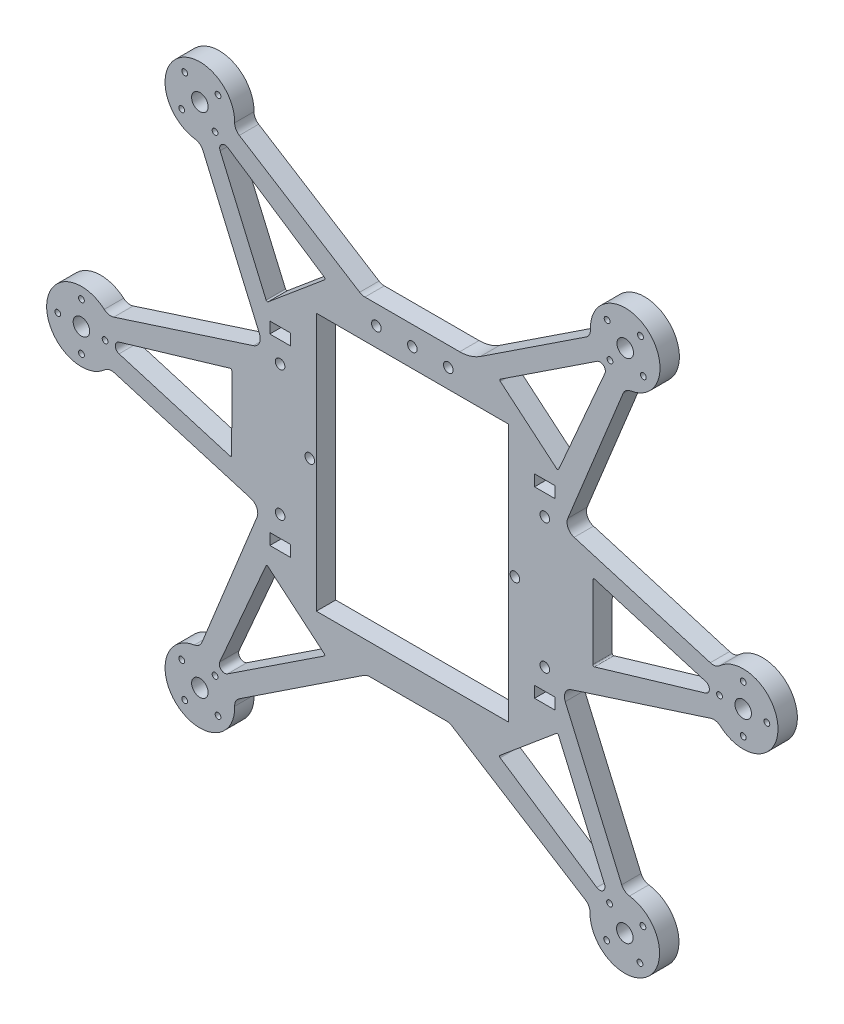
SolidWorks part; units mm, degrees
ref_plane "Front Plane" through (0, 0, 0) normal (0, 0, 1) x (1, 0, 0)
ref_plane "Top Plane" through (0, 0, 0) normal (0, 1, 0) x (1, 0, 0)
ref_plane "Right Plane" through (0, 0, 0) normal (1, 0, 0) x (0, 0, -1)
sketch "Sketch1" plane through (0, 0, 0) normal (0, 0, 1) x (1, 0, 0)
  line L0 (595.5776, 440.4192) -> (595.6011, 462.6566)
  line L1 (550.1603, 451.4897) -> (550.1603, 458.6435) construction
  line L2 (607.0986, 422.6607) -> (613.2986, 426.0607) construction
  line L3 (610.1986, 424.3607) -> (610.1986, 432.3607) construction
  line L4 (610.1986, 432.3607) -> (610.1986, 424.3607) construction
  line L5 (607.0986, 426.0607) -> (613.2986, 422.6607) construction
  line L6 (561.5223, 453.1038) -> (595.092, 463.0374)
  line L7 (561.5198, 450.0321) -> (595.073, 440.0434)
  line L8 (550.1603, 451.4897) -> (557.3141, 451.4897) construction
  line L9 (623.5557, 402.561) -> (606.5359, 416.873)
  line L10 (607.0986, 426.0607) -> (607.0986, 422.6607)
  line L11 (607.0986, 426.0607) -> (613.2986, 426.0607)
  line L12 (613.2986, 426.0607) -> (613.2986, 422.6607)
  line L13 (591.9484, 384.6267) -> (605.917, 416.7277)
  line L14 (603.9549, 476.5225) -> (586.8769, 515.9464)
  line L15 (594.2998, 382.6503) -> (623.5192, 401.9329)
  line L16 (607.0986, 422.6607) -> (613.2986, 422.6607)
  line L17 (706.0206, 520.3291) -> (676.8012, 501.0464)
  line L18 (635.8428, 502.057) -> (664.4776, 502.057)
  line L19 (592.0667, 518.4553) -> (605.9825, 486.3314)
  line L20 (637.2391, 403.4095) -> (660.5203, 403.4093)
  line L21 (690.1986, 470.2607) -> (690.1986, 433.8107) construction
  line L22 (693.2986, 481.4107) -> (687.0986, 478.0107) construction
  line L23 (690.1986, 479.7107) -> (690.1986, 471.7107) construction
  line L24 (550.1603, 451.4897) -> (550.1603, 444.3359) construction
  line L25 (676.7648, 500.4184) -> (693.7845, 486.1064)
  line L26 (597.8715, 525.3814) -> (634.2463, 502.5171)
  line L27 (690.1986, 471.7107) -> (690.1986, 479.7107) construction
  line L28 (714.5069, 528.0369) -> (719.9829, 523.4337) construction
  line L29 (650.0692, 451.5983) -> (-31455.4559, 38782.203) construction
  line L30 (606.5947, 486.1864) -> (623.6447, 500.4624)
  line L31 (594.4214, 520.4278) -> (623.6091, 501.0971)
  line L32 (619.1602, 451.4897) -> (621.1602, 451.4897) construction
  line L33 (621.1602, 490.4897) -> (679.1602, 490.4897)
  line L34 (650.5503, 451.9554) -> (-31454.9748, -37878.6493) construction
  line L35 (550.1603, 451.4897) -> (543.0064, 451.4897) construction
  line L36 (708.3721, 518.3527) -> (694.4034, 486.2517)
  line L37 (714.5069, 528.0369) -> (709.9037, 522.5609) construction
  line L38 (714.5069, 528.0369) -> (709.0308, 532.6402) construction
  line L39 (-349.7202, 451.4897) -> (49650.2798, 451.4897) construction
  line L40 (714.5069, 528.0369) -> (719.1101, 533.513) construction
  line L41 (670.7138, 503.9293) -> (702.6488, 525.004)
  line L42 (713.8498, 515.8148) -> (697.1476, 474.7902)
  line L43 (738.8006, 452.9472) -> (705.2474, 462.9359)
  line L44 (704.7428, 462.5601) -> (704.7193, 440.3227)
  line L45 (738.7981, 449.8755) -> (705.2284, 439.9419)
  line L46 (585.9492, 528.1509) -> (591.4334, 532.7444) construction
  line L47 (585.9492, 528.1509) -> (590.5427, 522.6667) construction
  line L48 (750.16, 451.4008) -> (750.1537, 444.247) construction
  line L49 (585.9492, 528.1509) -> (580.465, 523.5574) construction
  line L50 (585.9492, 528.1509) -> (581.3556, 533.6351) construction
  line L51 (750.16, 451.4008) -> (743.0062, 451.4072) construction
  line L52 (601.3009, 432.142) -> (560.1121, 444.3642)
  line L53 (559.9388, 458.8512) -> (602.1241, 472.4752)
  line L54 (750.16, 451.4008) -> (750.1664, 458.5547) construction
  line L55 (585.9492, 374.8285) -> (580.465, 379.422) construction
  line L56 (585.9492, 374.8285) -> (590.5428, 380.3127) construction
  line L57 (639.291, 496.2223) -> (661.0294, 496.2223) construction
  line L58 (679.1602, 490.4897) -> (679.1602, 412.4897)
  line L59 (585.9492, 374.8285) -> (591.4334, 370.235) construction
  line L60 (585.9492, 374.8285) -> (581.3557, 369.3443) construction
  line L61 (635.5822, 402.9105) -> (597.8019, 377.8824)
  line L62 (586.5847, 387.0517) -> (603.228, 428.1396)
  line L63 (750.16, 451.4008) -> (757.3138, 451.3945) construction
  line L64 (693.2986, 478.0107) -> (687.0986, 481.4107) construction
  line L65 (693.2986, 426.0607) -> (687.0986, 422.6607) construction
  line L66 (690.1986, 432.3607) -> (690.1986, 424.3607) construction
  line L67 (740.375, 444.048) -> (698.2123, 430.4725)
  line L68 (699.0702, 470.7837) -> (740.2145, 458.5351)
  line L69 (708.2537, 384.524) -> (694.3379, 416.6479)
  line L70 (690.1986, 424.3607) -> (690.1986, 432.3607) construction
  line L71 (693.7257, 416.7928) -> (676.6757, 402.5169)
  line L72 (621.1602, 490.4897) -> (621.1602, 412.4897)
  line L73 (705.899, 382.5515) -> (676.7113, 401.8822)
  line L74 (714.3708, 374.8282) -> (708.8866, 370.2347) construction
  line L75 (714.3708, 374.8282) -> (709.7772, 380.3124) construction
  line L76 (714.3708, 374.8282) -> (719.855, 379.4217) construction
  line L77 (714.3708, 374.8282) -> (718.9643, 369.344) construction
  line L78 (702.4485, 377.5977) -> (662.1168, 402.9492)
  line L79 (696.379, 426.4243) -> (713.4431, 387.0327)
  line L80 (621.1602, 412.4897) -> (679.1602, 412.4897)
  line L81 (681.1602, 451.4897) -> (679.1602, 451.4897) construction
  line L111 (650.1602, -499.8735) -> (650.1602, 49500.1265) construction
  line L113 (693.2986, 422.6607) -> (687.0986, 426.0607) construction
  line L115 (693.2986, 478.0107) -> (693.2986, 481.4107)
  line L116 (693.2986, 478.0107) -> (687.0986, 478.0107)
  line L117 (687.0986, 478.0107) -> (687.0986, 481.4107)
  line L118 (693.2986, 481.4107) -> (687.0986, 481.4107)
  line L119 (693.2986, 422.6607) -> (687.0986, 422.6607)
  line L120 (687.0986, 426.0607) -> (687.0986, 422.6607)
  line L121 (693.2986, 426.0607) -> (687.0986, 426.0607)
  line L122 (693.2986, 426.0607) -> (693.2986, 422.6607)
  line L157 (607.0986, 481.4107) -> (613.2986, 481.4107)
  line L158 (613.2986, 478.0107) -> (613.2986, 481.4107)
  line L159 (607.0986, 478.0107) -> (613.2986, 481.4107) construction
  line L160 (610.1986, 471.7107) -> (610.1986, 479.7107) construction
  line L161 (610.1986, 479.7107) -> (610.1986, 471.7107) construction
  line L162 (607.0986, 481.4107) -> (613.2986, 478.0107) construction
  line L163 (607.0986, 478.0107) -> (613.2986, 478.0107)
  line L164 (607.0986, 478.0107) -> (607.0986, 481.4107)
  line L165 (610.1986, 470.2607) -> (610.1986, 433.6599) construction
  line L318 (704.7429, 462.5602) -> (704.7193, 440.3227) [skipped]
  line L319 (738.7981, 449.8755) -> (705.2285, 439.942) [skipped]
  line L321 (738.8006, 452.9472) -> (705.2474, 462.936) [skipped]
  line L323 (705.8991, 382.5516) -> (676.7114, 401.8822) [skipped]
  line L324 (693.7258, 416.7929) -> (676.6758, 402.517) [skipped]
  line L325 (708.2537, 384.5241) -> (694.3379, 416.648) [skipped]
  circle A0 centre (550.1603, 451.4897) radius 2.5
  circle A1 centre (714.5069, 528.0369) radius 2.5
  circle A2 centre (585.9492, 528.1509) radius 2.5
  circle A3 centre (719.9829, 523.4337) radius 0.875
  arc A4 (595.092, 463.0374) -> (595.6011, 462.6566) centre (595.2045, 462.657) cw
  arc A5 (561.5198, 450.0321) -> (561.5223, 453.1038) centre (561.9769, 451.5676) cw
  arc A6 (595.5776, 440.4192) -> (595.073, 440.0434) centre (595.185, 440.4196) cw
  circle A7 centre (681.1602, 451.4897) radius 1.45
  arc A8 (606.5947, 486.1864) -> (605.9825, 486.3314) centre (606.3427, 486.4874) cw
  arc A9 (592.0667, 518.4553) -> (594.4214, 520.4278) centre (593.5368, 519.0921) cw
  arc A10 (605.917, 416.7277) -> (606.5359, 416.873) centre (606.2807, 416.5694) cw
  arc A11 (594.2998, 382.6503) -> (591.9484, 384.6267) centre (593.4174, 383.9874) cw
  arc A12 (623.5557, 402.561) -> (623.5192, 401.9329) centre (623.303, 402.2605) cw
  arc A13 (676.7648, 500.4184) -> (676.8012, 501.0464) centre (677.0174, 500.7188) cw
  circle A14 centre (550.1603, 458.6435) radius 0.875
  arc A15 (623.6091, 501.0971) -> (623.6447, 500.4624) centre (623.3901, 500.7664) cw
  circle A16 centre (619.1602, 451.4897) radius 1.45
  circle A17 centre (557.3141, 451.4897) radius 0.875
  arc A18 (694.4034, 486.2517) -> (693.7845, 486.1064) centre (694.0398, 486.41) cw
  arc A19 (706.0206, 520.3291) -> (708.3721, 518.3527) centre (706.903, 518.9919) cw
  circle A20 centre (709.9037, 522.5609) radius 0.875
  circle A21 centre (709.0308, 532.6402) radius 0.875
  circle A22 centre (661.0294, 496.2223) radius 1.45
  circle A23 centre (719.1101, 533.513) radius 0.875
  arc A24 (703.9942, 527.6253) -> (716.1576, 517.6465) centre (714.5069, 528.0369) cw
  circle A25 centre (750.16, 451.4008) radius 2.5
  circle A26 centre (750.1537, 444.247) radius 0.875
  arc A27 (704.7428, 462.5601) -> (705.2474, 462.9359) centre (705.1354, 462.5597) cw
  arc A28 (660.5203, 403.4093) -> (662.1168, 402.9492) centre (660.5203, 400.4093) cw
  arc A29 (693.7258, 416.7929) -> (694.3379, 416.648) centre (693.9778, 416.492) cw
  circle A30 centre (591.4334, 532.7444) radius 0.875
  circle A31 centre (590.5427, 522.6667) radius 0.875
  circle A32 centre (610.1986, 432.3607) radius 1.45
  circle A33 centre (690.1986, 471.7107) radius 1.45
  circle A34 centre (580.465, 523.5574) radius 0.875
  circle A35 centre (581.3556, 533.6351) radius 0.875
  arc A36 (705.2284, 439.9419) -> (704.7193, 440.3227) centre (705.1159, 440.3223) cw
  arc A37 (738.8006, 452.9472) -> (738.7981, 449.8755) centre (738.3435, 451.4117) cw
  arc A38 (584.529, 517.7264) -> (596.4684, 527.9723) centre (585.9492, 528.1509) cw
  circle A39 centre (550.1603, 444.3359) radius 0.875
  circle A40 centre (543.0064, 451.4897) radius 0.875
  arc A41 (557.2399, 443.7073) -> (557.0517, 459.4392) centre (550.1603, 451.4897) cw
  circle A42 centre (743.0062, 451.4072) radius 0.875
  circle A43 centre (750.1664, 458.5547) radius 0.875
  circle A44 centre (639.291, 496.2223) radius 1.45
  circle A46 centre (585.9492, 374.8285) radius 2.5
  circle A47 centre (580.465, 379.422) radius 0.875
  circle A48 centre (590.5428, 380.3127) radius 0.875
  circle A49 centre (591.4334, 370.235) radius 0.875
  circle A50 centre (581.3557, 369.3443) radius 0.875
  arc A51 (596.4612, 375.2587) -> (584.2801, 385.216) centre (585.9492, 374.8285) cw
  circle A52 centre (757.3138, 451.3945) radius 0.875
  arc A53 (743.0873, 459.1895) -> (743.2615, 443.4574) centre (750.16, 451.4008) cw
  circle A54 centre (714.3708, 374.8282) radius 2.5
  circle A55 centre (708.8866, 370.2347) radius 0.875
  arc A56 (693.7257, 416.7928) -> (694.3379, 416.6479) centre (693.9777, 416.4919) cw
  arc A57 (676.7113, 401.8822) -> (676.6757, 402.5169) centre (676.9303, 402.2128) cw
  arc A58 (708.2537, 384.524) -> (705.899, 382.5515) centre (706.7836, 383.8872) cw
  circle A59 centre (709.7772, 380.3124) radius 0.875
  circle A60 centre (719.855, 379.4217) radius 0.875
  circle A61 centre (718.9643, 369.344) radius 0.875
  arc A62 (715.7909, 385.2527) -> (703.8515, 375.0068) centre (714.3708, 374.8282) cw
  arc A63 (697.1476, 474.7902) -> (699.0702, 470.7837) centre (699.9262, 473.659) ccw
  arc A64 (635.5822, 402.9105) -> (637.2391, 403.4095) centre (637.2391, 400.4095) cw
  arc A65 (603.9549, 476.5225) -> (602.1241, 472.4752) centre (601.2021, 475.33) cw
  arc A66 (601.3009, 432.142) -> (603.228, 428.1396) centre (600.4475, 429.2659) cw
  arc A67 (635.8428, 502.057) -> (634.2463, 502.5171) centre (635.8428, 505.057) cw
  arc A68 (664.4776, 502.057) -> (670.7138, 503.9293) centre (664.4776, 513.379) ccw
  arc A69 (698.2123, 430.4725) -> (696.379, 426.4243) centre (699.1318, 427.6168) ccw
  arc A70 (703.9942, 527.6253) -> (702.6488, 525.004) centre (700.9964, 527.5079) cw
  arc A71 (716.1576, 517.6465) -> (713.8498, 515.8148) centre (716.6283, 514.6836) ccw
  arc A72 (743.0873, 459.1895) -> (740.2145, 458.5351) centre (741.0705, 461.4104) cw
  arc A73 (743.2615, 443.4574) -> (740.375, 444.048) centre (741.2944, 441.1924) ccw
  arc A74 (713.4431, 387.0327) -> (715.7909, 385.2527) centre (716.1959, 388.2252) ccw
  arc A75 (702.4485, 377.5977) -> (703.8515, 375.0068) centre (700.852, 375.0578) cw
  arc A76 (597.8019, 377.8824) -> (596.4612, 375.2587) centre (599.4587, 375.3814) ccw
  arc A77 (586.5847, 387.0517) -> (584.2801, 385.216) centre (583.8042, 388.178) cw
  arc A78 (560.1121, 444.3642) -> (557.2399, 443.7073) centre (559.2587, 441.4882) ccw
  arc A79 (559.9388, 458.8512) -> (557.0517, 459.4392) centre (559.0168, 461.706) cw
  arc A80 (596.4684, 527.9723) -> (597.8715, 525.3814) centre (599.468, 527.9213) ccw
  arc A81 (584.529, 517.7264) -> (586.8769, 515.9464) centre (584.1241, 514.7539) cw
  circle A82 centre (650.1602, 496.2223) radius 1.45
  circle A87 centre (690.1986, 432.3607) radius 1.45
  circle A129 centre (610.1986, 471.7107) radius 1.45
  arc A308 (705.2285, 439.942) -> (704.7193, 440.3227) centre (705.1159, 440.3223) cw [skipped]
  arc A309 (738.8006, 452.9472) -> (738.7981, 449.8755) centre (738.3435, 451.4118) cw [skipped]
  arc A310 (704.7429, 462.5602) -> (705.2474, 462.936) centre (705.1354, 462.5598) cw [skipped]
  arc A313 (676.7114, 401.8822) -> (676.6758, 402.517) centre (676.9304, 402.2129) cw [skipped]
  arc A314 (708.2537, 384.5241) -> (705.8991, 382.5516) centre (706.7837, 383.8873) cw [skipped]
  point P26 (606.1915, 485.8489)
  point P39 (610.1986, 451.9603)
  point P47 (650.1602, 451.4897)
  point P54 (615.1197, 493.3244)
  point P63 (624.0522, 500.8036)
  point P93 (650.1602, 502.057)
  point P104 (650.1602, 490.4897)
  point P238 (650.1602, 490.4897)
  point P239 (679.1602, 451.4897)
  point P240 (621.1602, 451.4897)
  point P357 (690.1986, 452.0357)
  point P366 (610.1986, 479.7107)
  dimension "D2" = 3
  dimension "D3" = 100
  dimension "D6" = 2
  dimension "D9" = 55.35
  dimension "D7" = 3
  dimension "D12" = 4
  dimension "D5" = 3
  dimension "D14" = 3
  dimension "D4" = 3
  dimension "D15" = 3
  dimension "D16" = 3
  dimension "D17" = 3
  dimension "D18" = 3
  dimension "D19" = 3
  dimension "D8" = 2
  dimension "D10" = 8
  dimension "D13" = 3
extrude "Boss-Extrude5" add sketch "Sketch1" along normal blind 5.85
